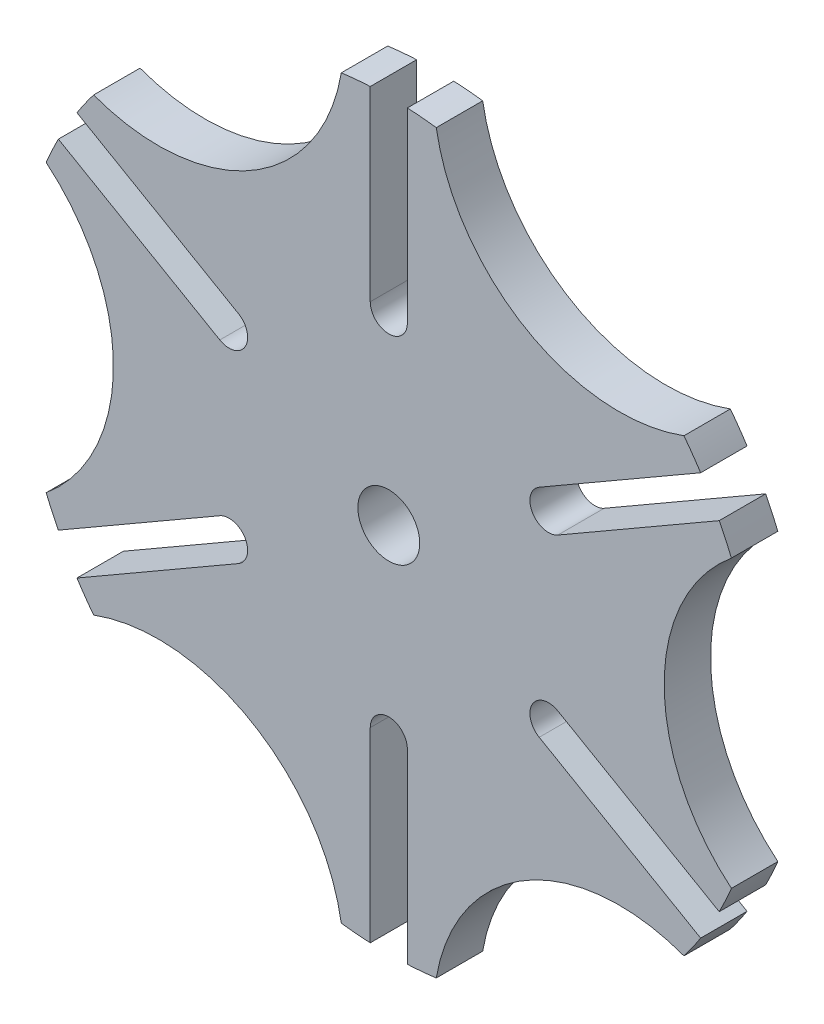
SolidWorks part; units mm, degrees
ref_plane "Front Plane" through (0, 0, 0) normal (0, 0, 1) x (1, 0, 0)
ref_plane "Top Plane" through (0, 0, 0) normal (0, 1, 0) x (1, 0, 0)
ref_plane "Right Plane" through (0, 0, 0) normal (1, 0, 0) x (0, 0, -1)
sketch "Sketch2" plane through (0, 0, 0) normal (0, 0, 1) x (1, 0, 0)
  line L0 (0, 0) -> (0, 76.2) construction
  line L1 (-3.81, 37.846) -> (-3.81, 76.1047)
  line L2 (3.81, 37.846) -> (3.81, 76.1047)
  line L3 (30.8706, 22.2226) -> (64.0036, 41.3519)
  line L4 (34.6806, 15.6234) -> (67.8136, 34.7528)
  line L5 (34.6806, -15.6234) -> (67.8136, -34.7528)
  line L6 (30.8706, -22.2226) -> (64.0036, -41.3519)
  line L7 (3.81, -37.846) -> (3.81, -76.1047)
  line L8 (-3.81, -37.846) -> (-3.81, -76.1047)
  line L9 (-30.8706, -22.2226) -> (-64.0036, -41.3519)
  line L10 (-34.6806, -15.6234) -> (-67.8136, -34.7528)
  line L11 (-34.6806, 15.6234) -> (-67.8136, 34.7528)
  line L12 (-30.8706, 22.2226) -> (-64.0036, 41.3519)
  line L13 (0, 0) -> (-152.3405, 0) construction
  circle A0 centre (0, 0) radius 6.35
  arc A1 (-67.8136, 34.7528) -> (-70.3209, 29.3497) centre (0, 0) ccw
  arc A3 (3.81, 37.846) -> (-3.81, 37.846) centre (0, 37.846) cw
  arc A4 (34.6806, 15.6234) -> (30.8706, 22.2226) centre (32.7756, 18.923) cw
  arc A5 (30.8706, -22.2226) -> (34.6806, -15.6234) centre (32.7756, -18.923) cw
  arc A6 (-3.81, -37.846) -> (3.81, -37.846) centre (0, -37.846) cw
  arc A7 (-34.6806, -15.6234) -> (-30.8706, -22.2226) centre (-32.7756, -18.923) cw
  arc A8 (-30.8706, 22.2226) -> (-34.6806, 15.6234) centre (-32.7756, 18.923) cw
  arc A9 (-70.3209, -29.3497) -> (-70.3209, 29.3497) centre (-94.615, 0) ccw
  arc A10 (-60.5781, 46.2248) -> (-9.7428, 75.5746) centre (-47.3075, 81.939) ccw
  arc A11 (9.7428, 75.5746) -> (60.5781, 46.2248) centre (47.3075, 81.939) ccw
  arc A12 (70.3209, 29.3497) -> (70.3209, -29.3497) centre (94.615, 0) ccw
  arc A13 (60.5781, -46.2248) -> (9.7428, -75.5746) centre (47.3075, -81.939) ccw
  arc A14 (-9.7428, -75.5746) -> (-60.5781, -46.2248) centre (-47.3075, -81.939) ccw
  arc A15 (-60.5781, 46.2248) -> (-64.0036, 41.3519) centre (0, 0) ccw
  arc A16 (-3.81, 76.1047) -> (-9.7428, 75.5746) centre (0, 0) ccw
  arc A17 (9.7428, 75.5746) -> (3.81, 76.1047) centre (0, 0) ccw
  arc A18 (64.0036, 41.3519) -> (60.5781, 46.2248) centre (0, 0) ccw
  arc A19 (70.3209, 29.3497) -> (67.8136, 34.7528) centre (0, 0) ccw
  arc A20 (60.5781, -46.2248) -> (64.0036, -41.3519) centre (0, 0) ccw
  arc A21 (-9.7428, -75.5746) -> (-3.81, -76.1047) centre (0, 0) ccw
  arc A22 (-64.0036, -41.3519) -> (-60.5781, -46.2248) centre (0, 0) ccw
  arc A23 (67.8136, -34.7528) -> (70.3209, -29.3497) centre (0, 0) ccw
  arc A24 (-70.3209, -29.3497) -> (-67.8136, -34.7528) centre (0, 0) ccw
  arc A25 (3.81, -76.1047) -> (9.7428, -75.5746) centre (0, 0) ccw
  point P37 (0, 0)
  point P58 (0, 0)
  dimension "D1" = 12.7
  dimension "D2" = 152.4
  dimension "D3" = 3.81
  dimension "D6" = 38.1
  dimension "D4" = 38.354
  dimension "D7" = 94.615
  dimension "D5" = 6
  dimension "D8" = 6
extrude "Boss-Extrude1" add sketch "Sketch2" along normal blind 9.525
sketch "Sketch3" plane through (0, 0, 0) normal (0, 0, -1) x (-1, 0, 0)
  circle A0 centre (0, 0) radius 6.35
  circle A1 centre (0, 0) radius 12.7
  dimension "D1" = 25.4
  dimension "D2" = 12.7
extrude "Boss-Extrude2" add sketch "Sketch3" along normal blind 9.525
